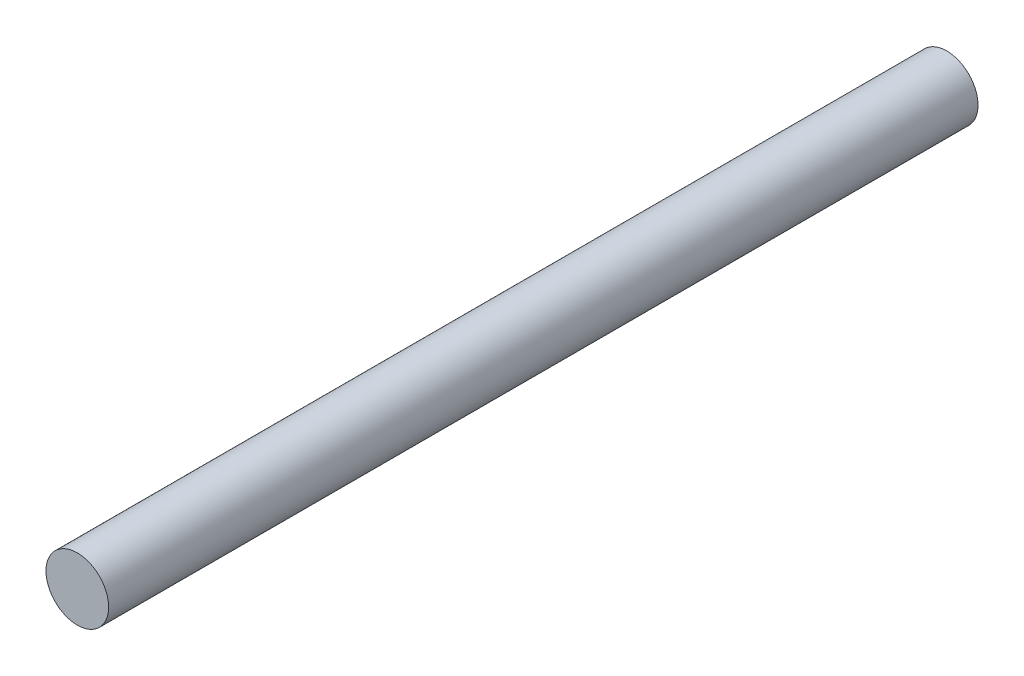
SolidWorks part; units mm, degrees
ref_plane "Front Plane" through (0, 0, 0) normal (0, 0, 1) x (1, 0, 0)
ref_plane "Top Plane" through (0, 0, 0) normal (0, 1, 0) x (1, 0, 0)
ref_plane "Right Plane" through (0, 0, 0) normal (1, 0, 0) x (0, 0, -1)
sketch "Sketch2" plane through (0, 0, 0) normal (0, 0, 1) x (1, 0, 0)
  circle A0 centre (0, 0) radius 1.5875
  dimension "D1" = 3.175
extrude "Boss-Extrude1" add sketch "Sketch2" along normal blind 44.07
